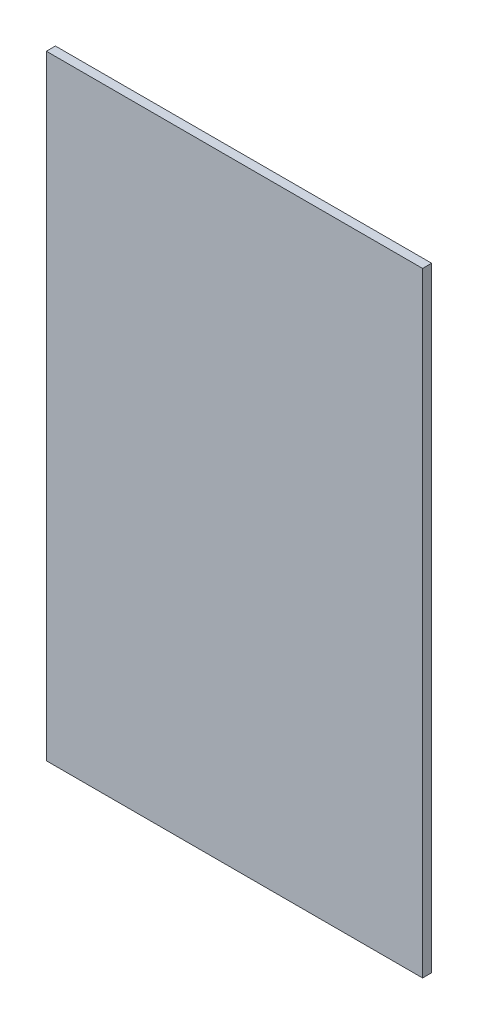
SolidWorks part; units mm, degrees
material "处理板，复杂型"
ref_plane "前视基准面" through (0, 0, 0) normal (0, 0, 1) x (1, 0, 0)
ref_plane "上视基准面" through (0, 0, 0) normal (0, 1, 0) x (1, 0, 0)
ref_plane "右视基准面" through (0, 0, 0) normal (1, 0, 0) x (0, 0, -1)
sketch "草图1" plane through (0, 0, 0) normal (0, 0, 1) x (1, 0, 0)
  line L1 (-64.5619, 50.451) -> (85.4381, 50.451)
  line L2 (-64.5619, 50.451) -> (-64.5619, -194.549)
  line L3 (-64.5619, -194.549) -> (85.4381, -194.549)
  line L4 (85.4381, 50.451) -> (85.4381, -194.549)
  dimension "D1" = 150
  dimension "D2" = 245
extrude "凸台-拉伸1" add sketch "草图1" along normal blind 3.6
